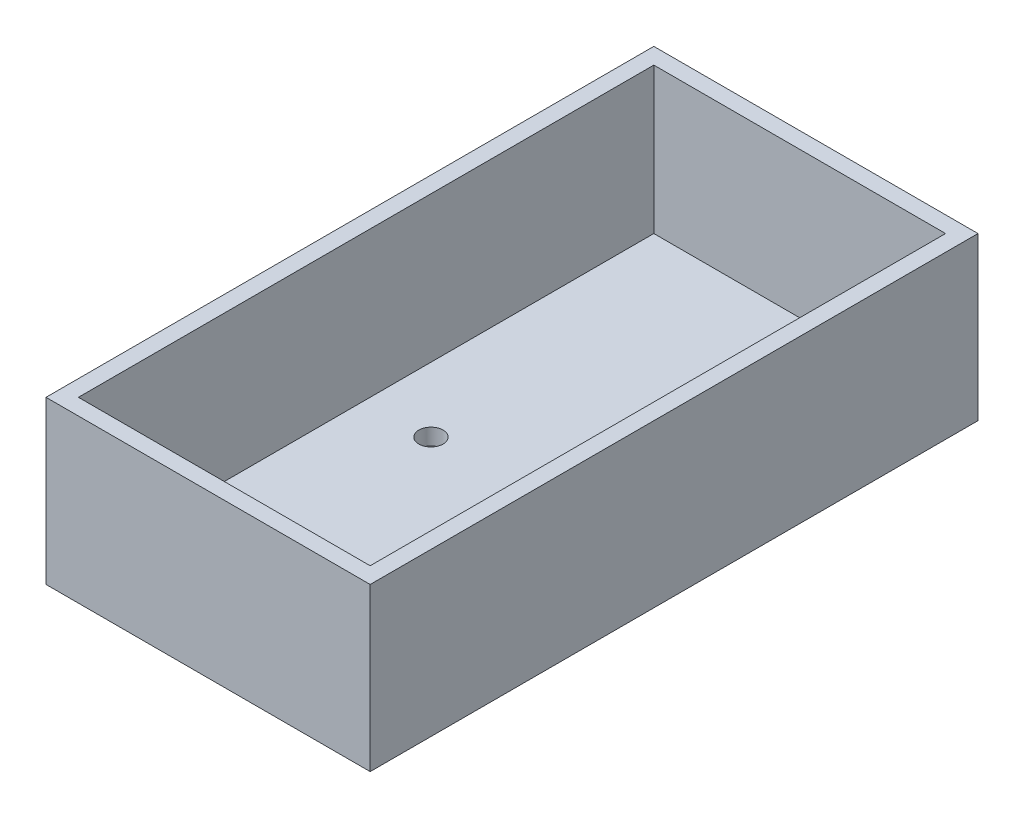
SolidWorks part; units mm, degrees
ref_plane "정면" through (0, 0, 0) normal (0, 0, 1) x (1, 0, 0)
ref_plane "윗면" through (0, 0, 0) normal (0, 1, 0) x (1, 0, 0)
ref_plane "우측면" through (0, 0, 0) normal (1, 0, 0) x (0, 0, -1)
sketch "스케치1" plane through (0, 0, 0) normal (0, 1, 0) x (1, 0, 0)
  line L1 (20, -37.5) -> (-20, -37.5)
  line L2 (20, -37.5) -> (20, 37.5)
  line L3 (20, 37.5) -> (-20, 37.5)
  line L4 (-20, -37.5) -> (-20, 37.5)
  point P5 (20, 0)
  point P8 (0, 37.5)
  dimension "D1" = 75
  dimension "D2" = 40
extrude "보스-돌출1" add sketch "스케치1" along normal blind 20
sketch "스케치2" plane through (0, 20, 0) normal (0, 1, 0) x (1, 0, 0)
  line L0 (-20, 37.5) -> (-20, -37.5) construction
  line L1 (-18, 35.5) -> (18, 35.5)
  line L2 (-18, 35.5) -> (-18, -35.5)
  line L3 (-18, -35.5) -> (18, -35.5)
  line L4 (18, 35.5) -> (18, -35.5)
  line L5 (-18, 35.5) -> (18, -35.5) construction
  line L6 (-18, -35.5) -> (18, 35.5) construction
  line L7 (20, 37.5) -> (-20, 37.5) construction
  point P0 (0, 0)
  dimension "D1" = 2
  dimension "D2" = 2
extrude "컷-돌출1" cut sketch "스케치2" against normal blind 18
sketch "Sketch1" plane through (0, 0, 0) normal (0, 1, 0) x (1, 0, 0)
  line L0 (0, -37.5) -> (0, 37.5) construction
  line L1 (-20, -37.5) -> (20, -37.5) construction
  line L2 (20, 37.5) -> (-20, 37.5) construction
  line L3 (-20, 0) -> (20, 0) construction
  line L4 (-20, 37.5) -> (-20, -37.5) construction
  line L5 (20, -37.5) -> (20, 37.5) construction
  circle A0 centre (-10, 0) radius 1.5
  circle A1 centre (10, 0) radius 1.5
  dimension "D1" = 3
  dimension "D2" = 20
extrude "Cut-Extrude4" cut sketch "Sketch1" against normal through all and the other way through all
